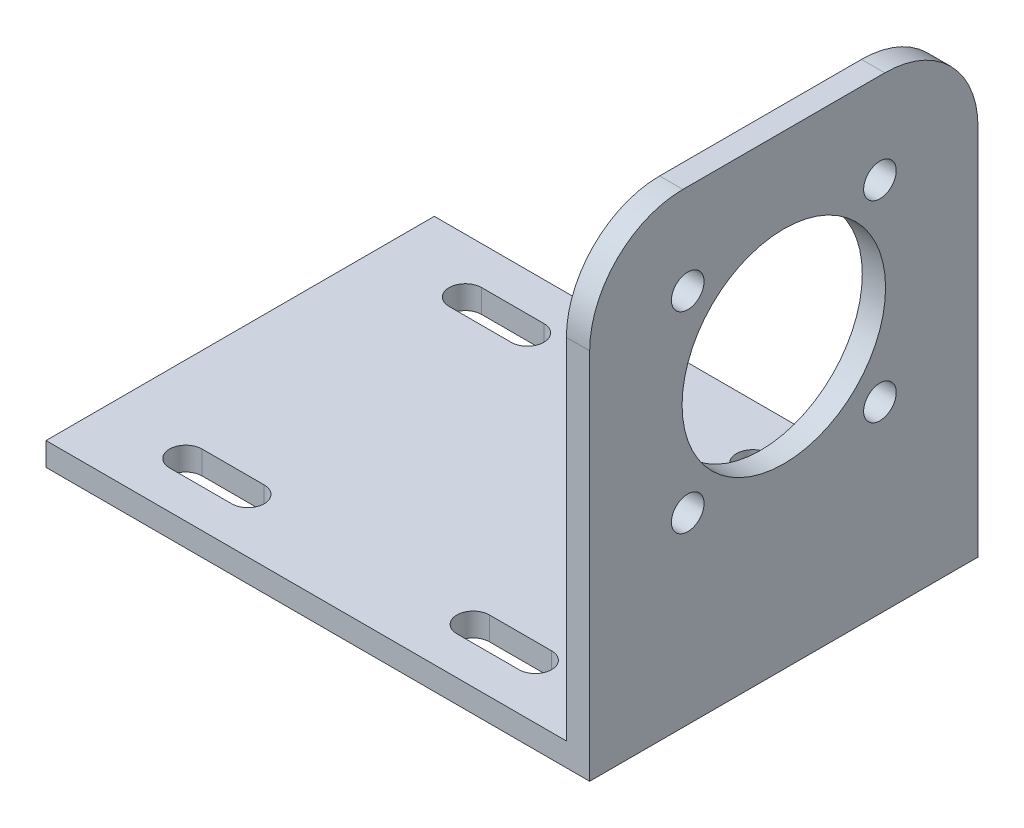
SolidWorks part; units mm, degrees
ref_plane "前视基准面" through (0, 0, 0) normal (0, 0, 1) x (1, 0, 0)
ref_plane "上视基准面" through (0, 0, 0) normal (0, 1, 0) x (1, 0, 0)
ref_plane "右视基准面" through (0, 0, 0) normal (1, 0, 0) x (0, 0, -1)
other "Configuration Table"
sketch "草图1" plane through (0, 0, 0) normal (0, 0, 1) x (1, 0, 0)
  line L0 (0, 0) -> (67, 0)
  line L1 (67, 0) -> (67, 57)
  line L2 (67, 57) -> (70, 57)
  line L3 (70, 57) -> (70, -3)
  line L4 (70, -3) -> (0, -3)
  line L5 (0, -3) -> (0, 0)
  dimension "D1" = 70
  dimension "D2" = 60
  dimension "D3" = 3
extrude "凸台-拉伸1" add sketch "草图1" along normal mid plane 50
sketch "草图2" plane through (0, 0, 0) normal (0, 1, 0) x (1, 0, 0)
  line L0 (-12.1207, 0) -> (77.3403, 0) construction
  line L1 (11, 18) -> (19, 18) construction
  line L2 (11, 20.1) -> (19, 20.1)
  line L3 (11, 15.9) -> (19, 15.9)
  line L4 (0, -25) -> (0, 25) construction
  line L5 (48, 18) -> (56, 18) construction
  line L6 (48, 20.1) -> (56, 20.1)
  line L7 (48, 15.9) -> (56, 15.9)
  line L8 (11, -18) -> (19, -18) construction
  line L9 (11, -20.1) -> (19, -20.1)
  line L10 (11, -15.9) -> (19, -15.9)
  line L11 (48, -18) -> (56, -18) construction
  line L12 (48, -20.1) -> (56, -20.1)
  line L13 (48, -15.9) -> (56, -15.9)
  arc A0 (11, 20.1) -> (11, 15.9) centre (11, 18) ccw
  arc A1 (19, 15.9) -> (19, 20.1) centre (19, 18) ccw
  arc A2 (48, 20.1) -> (48, 15.9) centre (48, 18) ccw
  arc A3 (56, 15.9) -> (56, 20.1) centre (56, 18) ccw
  arc A4 (11, -20.1) -> (11, -15.9) centre (11, -18) cw
  arc A5 (19, -15.9) -> (19, -20.1) centre (19, -18) cw
  arc A6 (48, -20.1) -> (48, -15.9) centre (48, -18) cw
  arc A7 (56, -15.9) -> (56, -20.1) centre (56, -18) cw
  point P5 (15, 18)
  point P14 (52, 18)
  point P21 (15, -18)
  point P28 (52, -18)
  dimension "D1" = 15
  dimension "D2" = 37
  dimension "D3" = 8
  dimension "D4" = 4.2
  dimension "D5" = 36
extrude "切除-拉伸1" cut sketch "草图2" against normal up to next
sketch "草图3" plane through (0, 0, 0) normal (1, 0, 0) x (0, 0, -1)
  line L0 (0, 69.3236) -> (0, -13.2469) construction
  line L1 (-51.1563, 33) -> (56.4802, 33) construction
  line L2 (-25, 57) -> (25, 57) construction
  circle A0 centre (0, 33) radius 17.5 construction
  circle A1 centre (0, 33) radius 13.1
  circle A2 centre (12.3744, 45.3744) radius 2.1
  circle A3 centre (12.3744, 20.6256) radius 2.1
  circle A4 centre (-12.3744, 20.6256) radius 2.1
  circle A5 centre (-12.3744, 45.3744) radius 2.1
  point P12 (0, 0)
  point P13 (0, 0)
  point P14 (0, 0)
  point P21 (0, 33)
  dimension "D1" = 35
  dimension "D2" = 26.2
  dimension "D4" = 4.2
  dimension "D3" = 24
  dimension "D5" = 4
extrude "切除-拉伸2" cut sketch "草图3" along normal up to next
fillet "圆角1" radius 12 2 edges at (68.5, 57, -25) (68.5, 57, 25)
